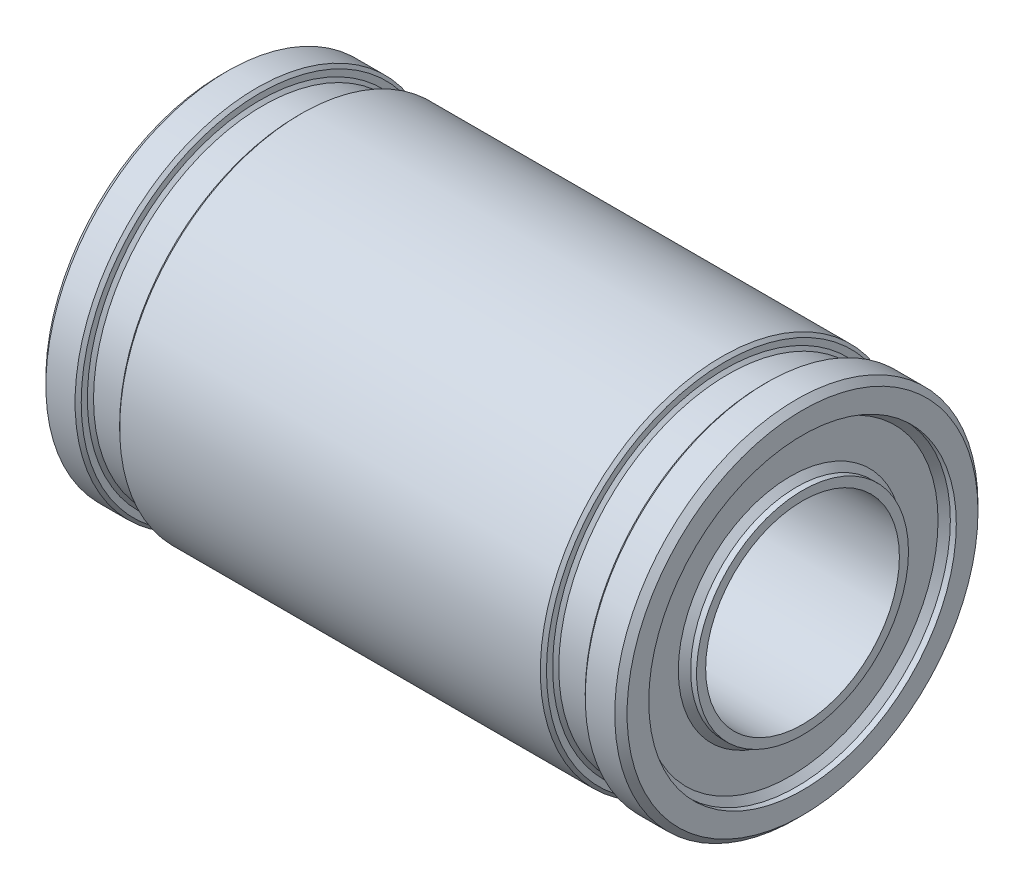
SolidWorks part; units mm, degrees
ref_plane "Front Plane" through (0, 0, 0) normal (0, 0, 1) x (1, 0, 0)
ref_plane "Top Plane" through (0, 0, 0) normal (0, 1, 0) x (1, 0, 0)
ref_plane "Right Plane" through (0, 0, 0) normal (1, 0, 0) x (0, 0, -1)
sketch "Sketch1" plane through (0, 0, 0) normal (0, 0, 1) x (1, 0, 0)
  line L0 (24, 6.35) -> (24, 7.246)
  line L1 (24, 7.246) -> (23.746, 7.5)
  line L2 (23.746, 7.5) -> (22.5268, 7.5)
  line L3 (22.5268, 7.5) -> (22.3998, 7.373)
  line L4 (22.3998, 7.373) -> (22.3998, 7.119)
  line L5 (22.3998, 7.119) -> (22.2728, 6.992)
  line L6 (22.2728, 6.992) -> (20.9266, 6.992)
  line L7 (20.9266, 6.992) -> (20.7996, 7.119)
  line L8 (20.7996, 7.119) -> (20.7996, 7.373)
  line L9 (20.7996, 7.373) -> (20.6726, 7.5)
  line L10 (20.6726, 7.5) -> (3.302, 7.5)
  line L11 (3.302, 7.5) -> (3.175, 7.373)
  line L12 (3.175, 7.373) -> (3.175, 7.119)
  line L13 (3.175, 7.119) -> (3.048, 6.992)
  line L14 (3.048, 6.992) -> (1.7145, 6.992)
  line L15 (1.7145, 6.992) -> (1.5875, 7.119)
  line L16 (1.5875, 7.119) -> (1.5875, 7.373)
  line L17 (1.5875, 7.373) -> (1.4605, 7.5)
  line L18 (1.4605, 7.5) -> (0.254, 7.5)
  line L19 (0.254, 7.5) -> (0, 7.246)
  line L20 (0, 7.246) -> (0, 6.35)
  line L21 (0, 6.35) -> (0.2563, 6.35)
  line L22 (0.2563, 6.35) -> (0.5103, 6.096)
  line L23 (0.5103, 6.096) -> (0.5103, 4.6295)
  line L24 (0.5103, 4.6295) -> (0.2563, 4.3755)
  line L25 (0.2563, 4.3755) -> (0, 4.3755)
  line L26 (0, 4.3755) -> (0, 4)
  line L27 (0, 4) -> (24, 4)
  line L28 (24, 4) -> (24, 4.3755)
  line L29 (24, 4.3755) -> (23.754, 4.3755)
  line L30 (23.754, 4.3755) -> (23.5, 4.6295)
  line L31 (23.5, 4.6295) -> (23.5, 6.096)
  line L32 (23.5, 6.096) -> (23.754, 6.35)
  line L33 (23.754, 6.35) -> (24, 6.35)
  line L34 (0, 0) -> (24, 0) construction
revolve "Revolve1" add sketch "Sketch1" angle 360 about L34
